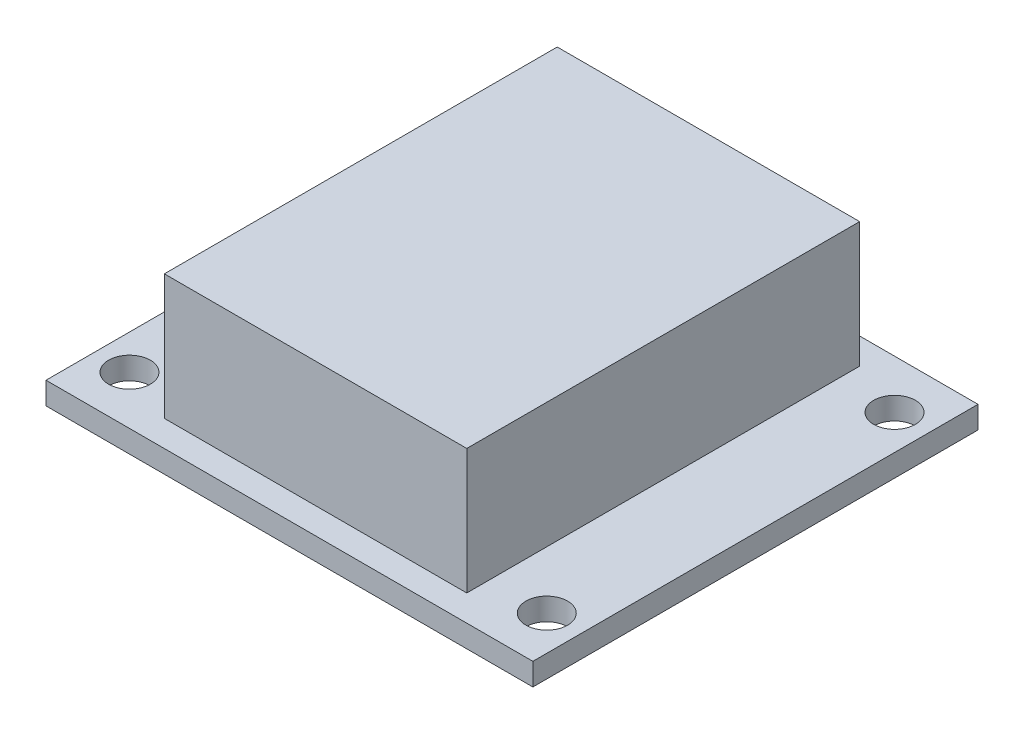
SolidWorks part; units mm, degrees
ref_plane "Front Plane" through (0, 0, 0) normal (0, 0, 1) x (1, 0, 0)
ref_plane "Top Plane" through (0, 0, 0) normal (0, 1, 0) x (1, 0, 0)
ref_plane "Right Plane" through (0, 0, 0) normal (1, 0, 0) x (0, 0, -1)
sketch "Sketch1" plane through (0, 0, 0) normal (0, 1, 0) x (1, 0, 0)
  line L0 (0, 16) -> (0, -16) construction
  line L1 (-17.5, -16) -> (17.5, -16)
  line L2 (-17.5, -16) -> (-17.5, 16)
  line L3 (-17.5, 16) -> (17.5, 16)
  line L4 (17.5, -16) -> (17.5, 16)
  line L5 (-17.5, -16) -> (17.5, 16) construction
  line L6 (-17.5, 16) -> (17.5, -16) construction
  line L7 (-17.5, 0) -> (17.5, 0) construction
  circle A0 centre (-15, 12.5) radius 1.5
  circle A1 centre (15, 12.5) radius 1.5
  circle A2 centre (15, -12.5) radius 1.5
  circle A3 centre (-15, -12.5) radius 1.5
  point P0 (0, 0)
  dimension "D3" = 3
  dimension "D1" = 35
  dimension "D2" = 32
  dimension "D4" = 3.5
  dimension "D5" = 2.5
extrude "Boss-Extrude1" add sketch "Sketch1" along normal blind 1.6
sketch "Sketch2" plane through (0, 1.6, 0) normal (0, 1, 0) x (1, 0, 0)
  line L1 (-10.8704, -14.1219) -> (10.8704, -14.1219)
  line L2 (-10.8704, -14.1219) -> (-10.8704, 14.1219)
  line L3 (-10.8704, 14.1219) -> (10.8704, 14.1219)
  line L4 (10.8704, -14.1219) -> (10.8704, 14.1219)
  line L5 (-10.8704, -14.1219) -> (10.8704, 14.1219) construction
  line L6 (-10.8704, 14.1219) -> (10.8704, -14.1219) construction
  point P0 (0, 0)
extrude "Boss-Extrude2" add sketch "Sketch2" along normal blind 9
